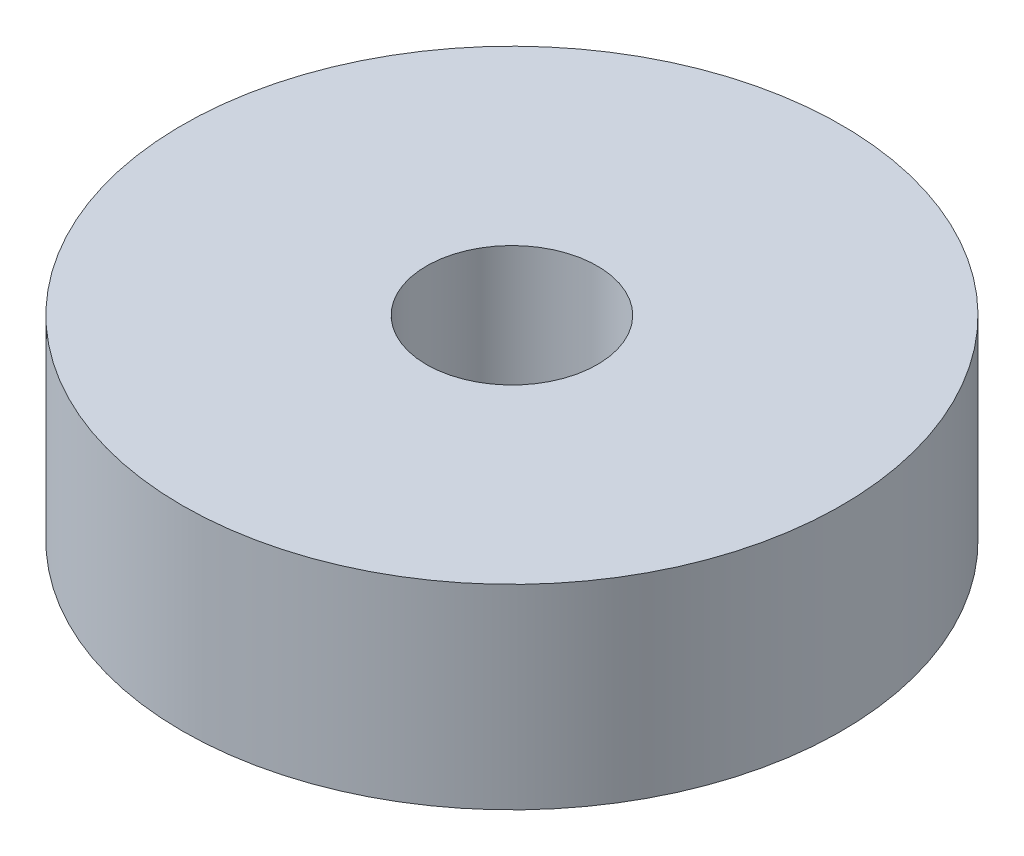
SolidWorks part; units mm, degrees
ref_plane "Front Plane" through (0, 0, 0) normal (0, 0, 1) x (1, 0, 0)
ref_plane "Top Plane" through (0, 0, 0) normal (0, 1, 0) x (1, 0, 0)
ref_plane "Right Plane" through (0, 0, 0) normal (1, 0, 0) x (0, 0, -1)
sketch "Sketch1" plane through (0, 0, 0) normal (0, 1, 0) x (1, 0, 0)
  circle A0 centre (0, 0) radius 1.75
  circle A1 centre (0, 0) radius 6.75
  dimension "D1" = 3.5
  dimension "D2" = 5
extrude "Boss-Extrude1" add sketch "Sketch1" along normal blind 4
